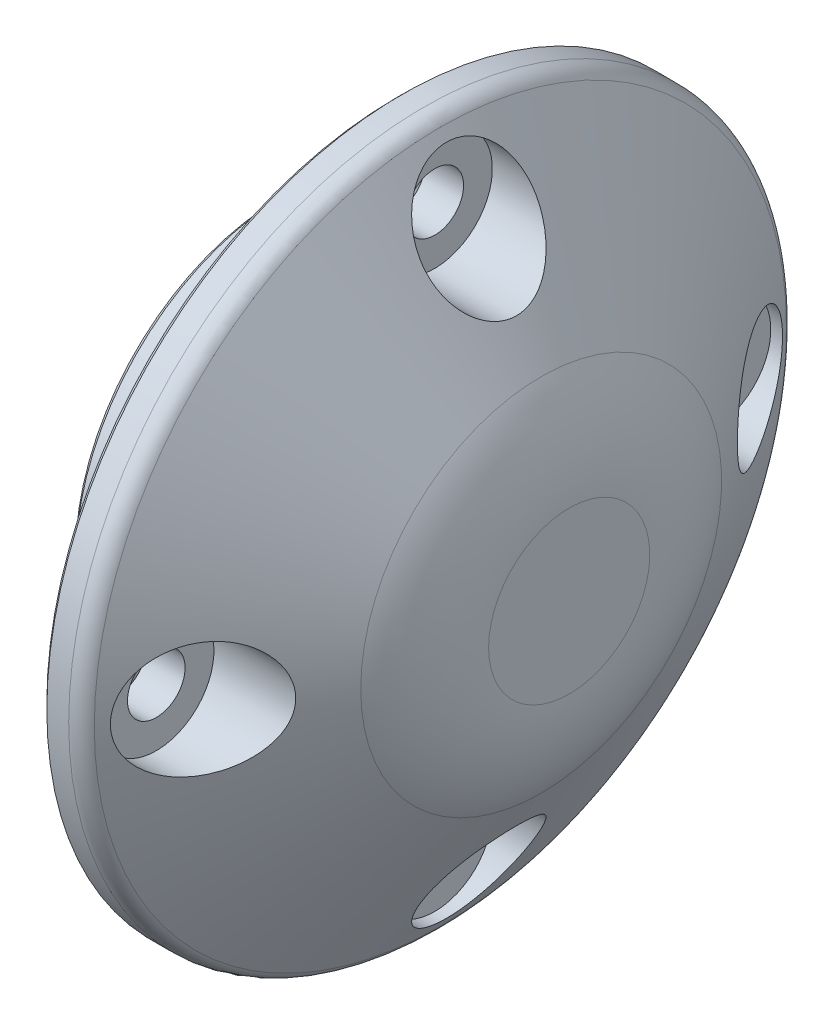
SolidWorks part; units mm, degrees
ref_plane "Front Plane" through (0, 0, 0) normal (0, 0, 1) x (1, 0, 0)
ref_plane "Top Plane" through (0, 0, 0) normal (0, 1, 0) x (1, 0, 0)
ref_plane "Right Plane" through (0, 0, 0) normal (1, 0, 0) x (0, 0, -1)
sketch "Sketch1" plane through (0, 0, 0) normal (0, 0, 1) x (1, 0, 0)
  line L0 (0, 0) -> (26.2994, 0) construction
  line L1 (-6, 9) -> (-6, 11)
  line L2 (-6, 11) -> (0, 11)
  line L3 (0, 11) -> (0, 18.5)
  line L4 (0, 18.5) -> (1.438, 18.5)
  line L7 (2, 0) -> (9, 0)
  line L8 (9, 4.1958) -> (9, 0)
  line L9 (2.2922, 18.0199) -> (7.542, 9.3953)
  line L10 (2, 9) -> (2, 0)
  line L11 (2, 9) -> (-6, 9)
  arc A1 (9, 4.1958) -> (7.542, 9.3953) centre (-1, 4.1958) ccw
  arc A2 (1.438, 18.5) -> (2.2922, 18.0199) centre (1.438, 17.5) cw
  point P12 (9, 7)
  point P17 (2, 18.5)
  dimension "D6" = 7
  dimension "D8" = 10
  dimension "D9" = 1
  dimension "D1" = 6
  dimension "D2" = 11
  dimension "D3" = 18.5
  dimension "D4" = 2
  dimension "D5" = 2
  dimension "D7" = 7
  dimension "D11" = 9
  dimension "D12" = 2
revolve "Revolve1" add sketch "Sketch1" angle 360 about L0
fillet "Fillet2" radius 1 2 edges at (2, 0, 9) (0, 0, 11)
chamfer "Chamfer1" distance 0.3 angle 45 2 edges at (-6, 0, 11) (0, 0, 18.5)
sketch "Sketch2" plane through (0, 0, 0) normal (-1, 0, 0) x (0, 0, 1)
  circle A0 centre (0, 14.5) radius 1.5
  circle A1 centre (14.5, 0) radius 1.5
  circle A2 centre (0, -14.5) radius 1.5
  circle A3 centre (-14.5, 0) radius 1.5
  point P12 (0, 0)
  dimension "D2" = 3
  dimension "D114.5" = 14.5
  dimension "D3" = 4
extrude "Cut-Extrude1" cut sketch "Sketch2" against normal blind 10
ref_plane "Plane1" through (2, 0, 0) normal (-1, 0, 0) x (0, 0, 1)
sketch "Sketch3" plane through (2, 0, 0) normal (-1, 0, 0) x (0, 0, 1)
  circle A0 centre (0, 14.5) radius 3
  circle A1 centre (14.5, 0) radius 3
  circle A2 centre (0, -14.5) radius 3
  circle A3 centre (-14.5, 0) radius 3
  circle A4 centre (0, 14.5) radius 1.5 construction
  point P12 (0, 0)
  dimension "D2" = 6
  dimension "D3" = 4
extrude "Cut-Extrude2" cut sketch "Sketch3" against normal blind 10
